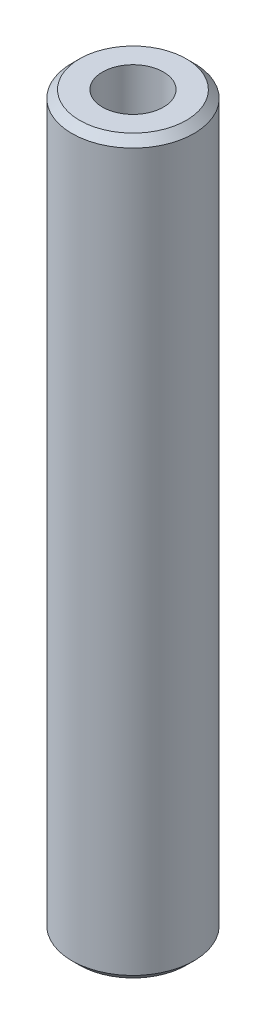
SolidWorks part; units mm, degrees
ref_plane "Front Plane" through (0, 0, 0) normal (0, 0, 1) x (1, 0, 0)
ref_plane "Top Plane" through (0, 0, 0) normal (0, 1, 0) x (1, 0, 0)
ref_plane "Right Plane" through (0, 0, 0) normal (1, 0, 0) x (0, 0, -1)
sketch "Sketch1" plane through (0, 0, 0) normal (0, 1, 0) x (1, 0, 0)
  circle A1 centre (0, 0) radius 2
  circle A2 centre (0, 0) radius 4
  dimension "D1" = 4
  dimension "D2" = 2
extrude "Boss-Extrude1" add sketch "Sketch1" along normal blind 48
chamfer "Chamfer1" distance 0.5 angle 45 2 edges at (0, 0, 4) (0, 48, 4)
